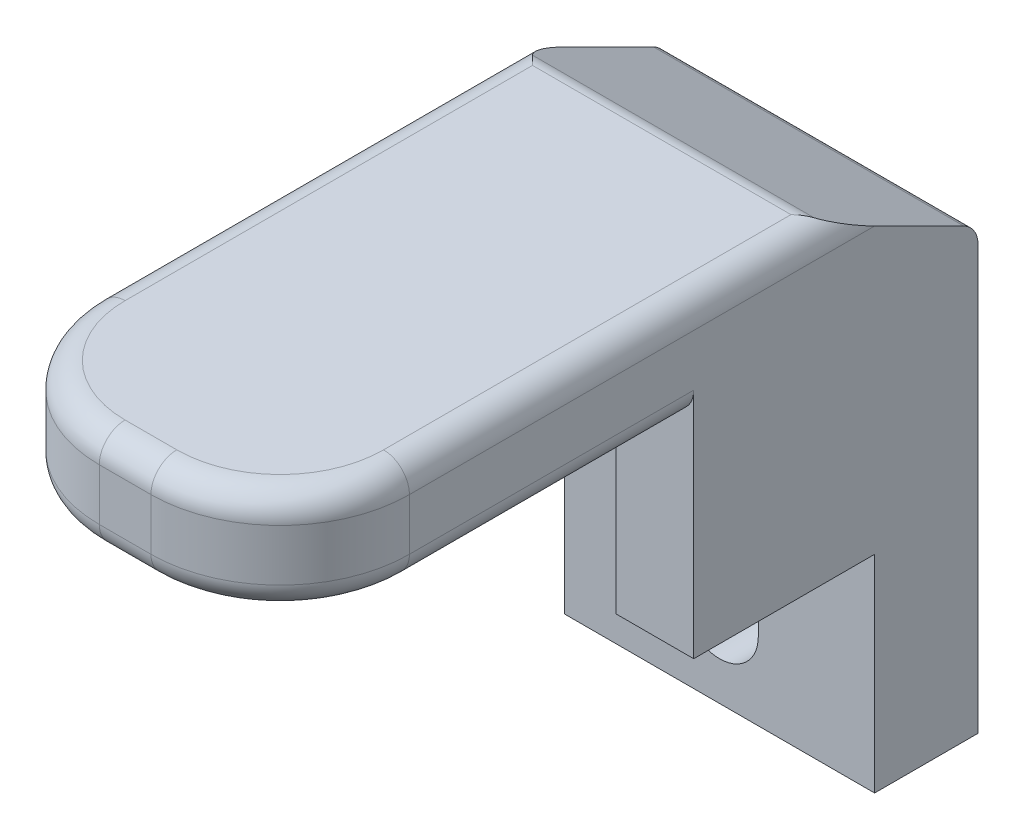
SolidWorks part; units mm, degrees
ref_plane "前视基准面" through (0, 0, 0) normal (0, 0, 1) x (1, 0, 0)
ref_plane "上视基准面" through (0, 0, 0) normal (0, 1, 0) x (1, 0, 0)
ref_plane "右视基准面" through (0, 0, 0) normal (1, 0, 0) x (0, 0, -1)
sketch "草图2" plane through (0, 0, 0) normal (0, 0, 1) x (1, 0, 0)
  line L0 (7.4498, 20.9633) -> (7.4498, 11.9997) construction
  line L1 (5.9498, 6.4997) -> (5.9498, 2.9997)
  line L2 (5.9498, 11.9997) -> (8.9498, 11.9997)
  line L3 (5.9498, 16.9997) -> (5.9498, 11.9997)
  line L4 (8.9498, 16.9997) -> (8.9498, 11.9997)
  line L6 (5.9498, 6.4997) -> (8.9498, 6.4997)
  line L8 (7.4498, 6.4997) -> (7.4498, 1.9666) construction
  line L9 (8.9498, 6.4997) -> (8.9498, 2.9997)
  line L13 (13.4498, 19.9997) -> (1.4498, 19.9997)
  line L14 (1.4498, 19.9997) -> (1.4498, -0.0003)
  line L15 (1.4498, -0.0003) -> (13.4498, -0.0003)
  line L16 (13.4498, -0.0003) -> (13.4498, 19.9997)
  arc A0 (8.9498, 16.9997) -> (5.9498, 16.9997) centre (7.4498, 16.9997) ccw
  arc A1 (5.9498, 2.9997) -> (8.9498, 2.9997) centre (7.4498, 2.9997) ccw
  dimension "D1" = 3
  dimension "D3" = 3
  dimension "D2" = 20
  dimension "D4" = 12
  dimension "D5" = 6
  dimension "D6" = 3
  dimension "D7" = 14
  dimension "D8" = 3.5
  dimension "D9" = 5
extrude "凸台-拉伸1" add sketch "草图2" along normal blind 4
sketch "草图3" plane through (0, 0, 4) normal (0, 0, 1) x (1, 0, 0)
  line L0 (1.4498, 19.9997) -> (1.4498, -0.0003) construction
  line L1 (1.4498, 19.9997) -> (13.4498, 19.9997)
  line L2 (1.4498, 19.9997) -> (1.4498, 15.9997)
  line L3 (1.4498, 15.9997) -> (13.4498, 15.9997)
  line L4 (13.4498, 19.9997) -> (13.4498, 15.9997)
  line L5 (13.4498, -0.0003) -> (13.4498, 19.9997) construction
  line L7 (1.4498, -0.0003) -> (13.4498, -0.0003) construction
  dimension "D2" = 16
extrude "凸台-拉伸2" add sketch "草图3" along normal blind 23 and the other way up to surface
sketch "草图4" plane through (0, 0, 4) normal (0, 0, 1) x (1, 0, 0)
  line L0 (1.4498, 15.9997) -> (1.4498, -0.0003) construction
  line L1 (1.4498, 15.9997) -> (4.4498, 15.9997)
  line L2 (1.4498, 15.9997) -> (1.4498, 7.9997)
  line L3 (1.4498, 7.9997) -> (4.4498, 7.9997)
  line L4 (4.4498, 15.9997) -> (4.4498, 7.9997)
  line L6 (10.4498, 15.9997) -> (13.4498, 15.9997)
  line L7 (10.4498, 15.9997) -> (10.4498, 7.9997)
  line L8 (10.4498, 7.9997) -> (13.4498, 7.9997)
  line L9 (13.4498, 15.9997) -> (13.4498, 7.9997)
  line L10 (13.4498, -0.0003) -> (13.4498, 15.9997) construction
  line L11 (13.4498, 19.9997) -> (1.4498, 19.9997) construction
  dimension "D1" = 3
  dimension "D2" = 3
  dimension "D3" = 8
  dimension "D4" = 8
  dimension "D5" = 4
  dimension "D6" = 4
extrude "凸台-拉伸3" add sketch "草图4" along normal blind 7
ref_plane "基准面3" through (7.4498, 0, 0) normal (1, 0, 0) x (0, 0, -1)
fillet "圆角5" radius 5 2 edges at (13.4498, 17.9997, 27) (1.4498, 17.9997, 27)
sketch "草图8" plane through (1.4498, 0, 0) normal (-1, 0, 0) x (0, 0, 1)
  line L0 (0, 16.9997) -> (6, 19.9997)
  line L1 (0, 19.9997) -> (0, -0.0003) construction
  line L2 (22, 19.9997) -> (0, 19.9997) construction
  line L3 (0, 16.9997) -> (0, 19.9997)
  line L4 (0, 19.9997) -> (6, 19.9997)
  dimension "D1" = 3
  dimension "D2" = 6
extrude "切除-拉伸2" cut sketch "草图8" against normal through all
fillet "圆角6" radius 1 12 edges at (1.4498, 19.9997, 14) (13.4498, 19.9997, 14) (11.9853, 19.9997, 25.5355) (7.4498, 19.9997, 27) (13.4498, 15.9997, 16.5) (11.9853, 15.9997, 25.5355) (7.4498, 15.9997, 27) (1.4498, 15.9997, 16.5) (2.9143, 19.9997, 25.5355) (2.9143, 15.9997, 25.5355) (7.4498, 19.9997, 6) (7.4498, 16.9997, 0)
